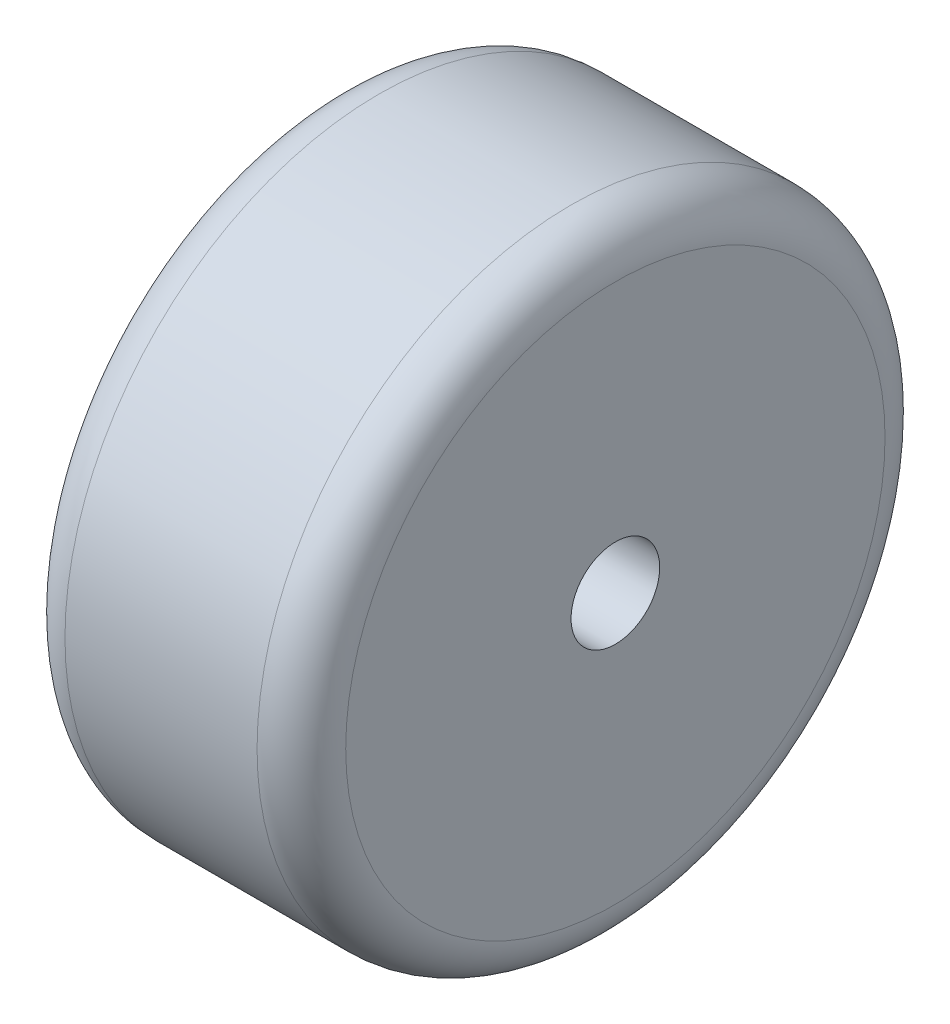
SolidWorks part; units mm, degrees
ref_plane "Спереди" through (0, 0, 0) normal (0, 0, 1) x (1, 0, 0)
ref_plane "Сверху" through (0, 0, 0) normal (0, 1, 0) x (1, 0, 0)
ref_plane "Справа" through (0, 0, 0) normal (1, 0, 0) x (0, 0, -1)
sketch "Sketch1" plane through (0, 0, 0) normal (1, 0, 0) x (0, 0, -1)
  circle A0 centre (0, 0) radius 42.5
extrude "Boss-Extrude1" add sketch "Sketch1" along normal blind 38
fillet "Fillet2" radius 6 2 edges at (0, 0, -42.5) (38, 0, -42.5)
sketch "Sketch2" plane through (38, 0, 0) normal (1, 0, 0) x (0, 0, -1)
  circle A0 centre (0, 0) radius 6
  point P4 (-8.4782, -0.2215)
extrude "Cut-Extrude2" cut sketch "Sketch2" against normal blind 38
